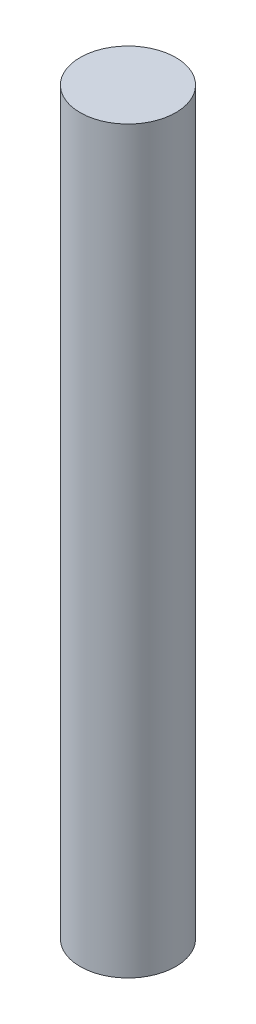
SolidWorks part; units mm, degrees
ref_plane "Front Plane" through (0, 0, 0) normal (0, 0, 1) x (1, 0, 0)
ref_plane "Top Plane" through (0, 0, 0) normal (0, 1, 0) x (1, 0, 0)
ref_plane "Right Plane" through (0, 0, 0) normal (1, 0, 0) x (0, 0, -1)
sketch "Sketch1" plane through (0, 0, 0) normal (0, 1, 0) x (1, 0, 0)
  circle A0 centre (0, 0) radius 1.5
  dimension "D1" = 3
extrude "Boss-Extrude1" add sketch "Sketch1" along normal blind 23.2
